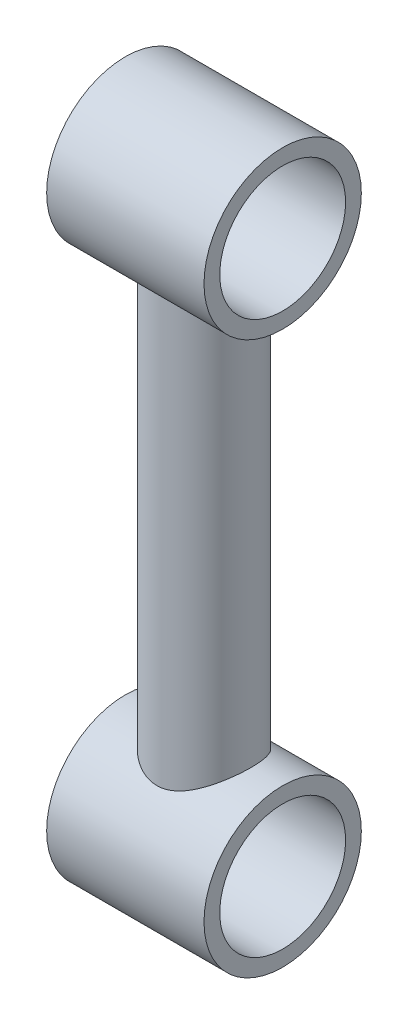
SolidWorks part; units mm, degrees
ref_plane "前视基准面" through (0, 0, 0) normal (0, 0, 1) x (1, 0, 0)
ref_plane "上视基准面" through (0, 0, 0) normal (0, 1, 0) x (1, 0, 0)
ref_plane "右视基准面" through (0, 0, 0) normal (1, 0, 0) x (0, 0, -1)
sketch "草图1" plane through (0, 0, 0) normal (1, 0, 0) x (0, 0, -1)
  circle A0 centre (0, 0) radius 50
  circle A1 centre (0, 0) radius 40
extrude "凸台-拉伸1" add sketch "草图1" against normal mid plane 100
ref_plane "基准面2" through (0, -175.6, 0) normal (0, 1, 0) x (1, 0, 0)
sketch "草图2" plane through (0, -175.6, 0) normal (0, 1, 0) x (1, 0, 0)
  circle A0 centre (0, 0) radius 30
extrude "凸台-拉伸2" add sketch "草图2" along normal up to surface (135.6 mm away) contours A0
mirror "镜向4" about plane through (0, -175.6, 0) normal (0, 1, 0) of "凸台-拉伸1", "凸台-拉伸2"
mirror "镜向5" about plane through (0, -175.6, 0) normal (0, 1, 0) of "凸台-拉伸1"
